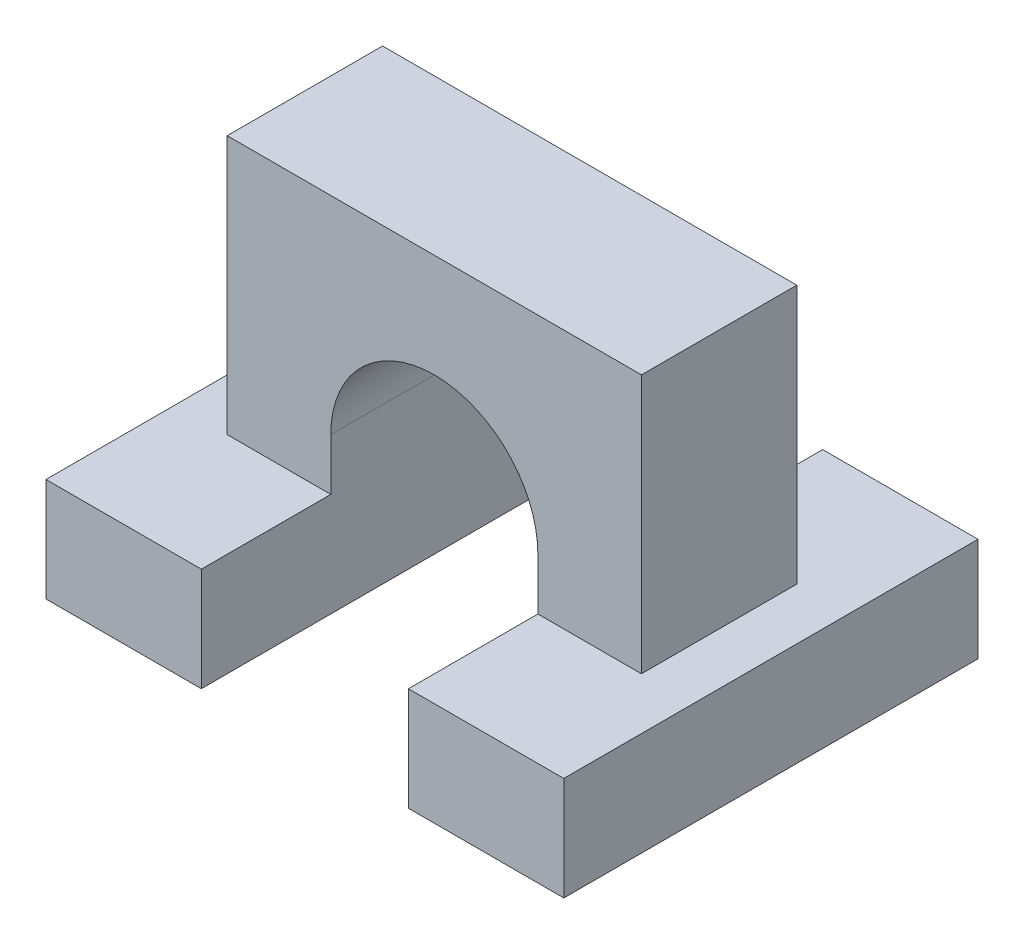
SolidWorks part; units mm, degrees
ref_plane "Front Plane" through (0, 0, 0) normal (0, 0, 1) x (1, 0, 0)
ref_plane "Top Plane" through (0, 0, 0) normal (0, 1, 0) x (1, 0, 0)
ref_plane "Right Plane" through (0, 0, 0) normal (1, 0, 0) x (0, 0, -1)
sketch "Sketch1" plane through (0, 0, 0) normal (0, 0, 1) x (1, 0, 0)
  line L0 (0, 34500) -> (0, -35500) construction
  line L1 (-34500, 0) -> (35500, 0) construction
  line L2 (-10000, 0) -> (-10000, -5000)
  line L3 (10000, 0) -> (10000, -5000)
  line L4 (10000, -5000) -> (20000, -5000)
  line L5 (20000, -5000) -> (20000, 20000)
  line L6 (20000, 20000) -> (-20000, 20000)
  line L7 (-20000, 20000) -> (-20000, -5000)
  line L8 (-20000, -5000) -> (-10000, -5000)
  arc A0 (10000, 0) -> (-10000, 0) centre (0, 0) ccw
  point P9 (0, 0)
  dimension "D1" = 10000
  dimension "D2" = 5000
  dimension "D3" = 5000
  dimension "D4" = 10000
  dimension "D5" = 10000
  dimension "D6" = 40000
  dimension "D7" = 20000
extrude "Boss-Extrude1" add sketch "Sketch1" along normal blind 15000
sketch "Sketch2" plane through (0, -5000, 0) normal (0, -1, 0) x (1, 0, 0)
  line L0 (10000, 27500) -> (25000, 27500)
  line L1 (25000, 27500) -> (25000, -12500)
  line L2 (25000, -12500) -> (10000, -12500)
  line L3 (10000, -12500) -> (10000, 27500)
  line L6 (-25000, 27500) -> (-10000, 27500)
  line L7 (-10000, 27500) -> (-10000, -12500)
  line L8 (-10000, -12500) -> (-25000, -12500)
  line L9 (-25000, -12500) -> (-25000, 27500)
  dimension "D1" = 15000
  dimension "D2" = 40000
  dimension "D3" = 12500
  dimension "D4" = 15000
  dimension "D5" = 40000
  dimension "D6" = 12500
extrude "Boss-Extrude2" add sketch "Sketch2" along normal blind 10000
